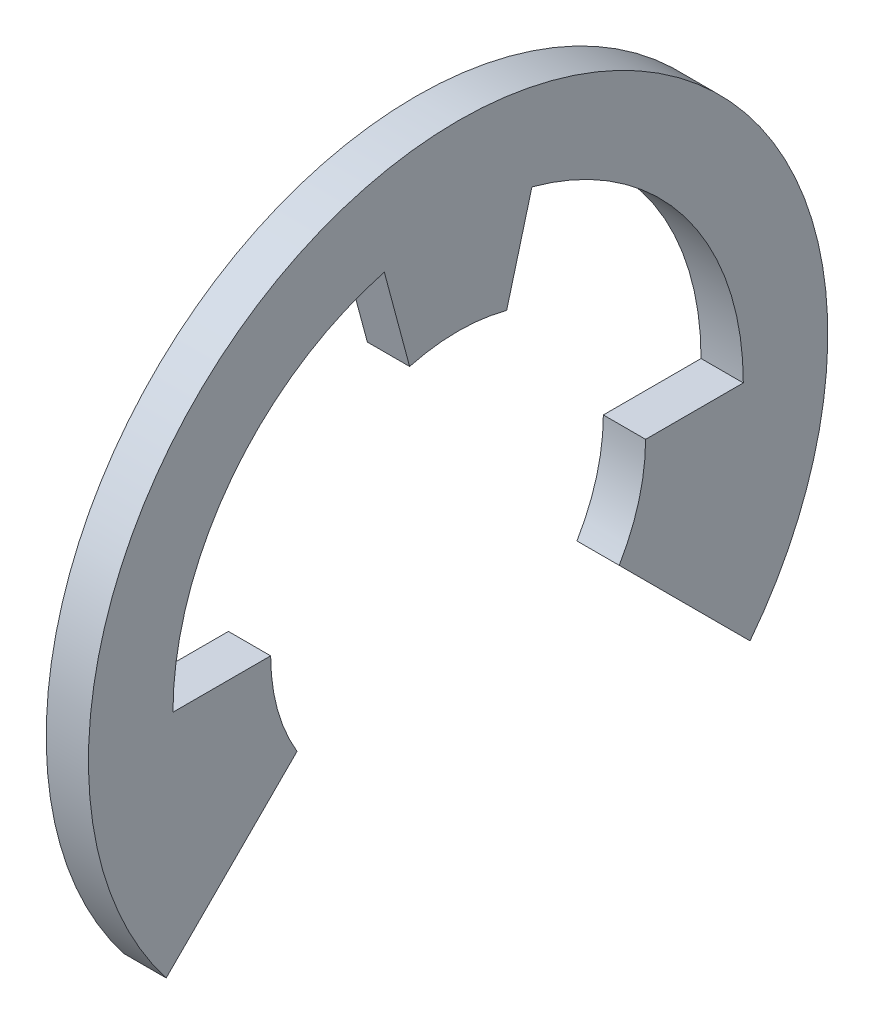
SolidWorks part; units mm, degrees
ref_plane "Front Plane" through (0, 0, 0) normal (0, 0, 1) x (1, 0, 0)
ref_plane "Top Plane" through (0, 0, 0) normal (0, 1, 0) x (1, 0, 0)
ref_plane "Right Plane" through (0, 0, 0) normal (1, 0, 0) x (0, 0, -1)
sketch "Sketch1" plane through (0, 0, 0) normal (1, 0, 0) x (0, 0, -1)
  line L0 (-3.55, 0) -> (-5.4, 0)
  line L1 (-0.9188, 3.429) -> (-1.3976, 5.216)
  line L2 (3.55, 0) -> (5.4, 0)
  line L3 (1.3976, 5.216) -> (0.9188, 3.429)
  line L4 (-3.05, -1.8166) -> (-5.5279, -4.2945)
  line L5 (3.05, -1.8166) -> (5.5279, -4.2945)
  line L9 (0, 0) -> (0, 7) construction
  arc A0 (-3.55, 0) -> (-3.05, -1.8166) centre (0, 0) ccw
  arc A1 (5.5279, -4.2945) -> (-5.5279, -4.2945) centre (0, 0) ccw
  arc A2 (5.4, 0) -> (1.3976, 5.216) centre (0, 0) ccw
  arc A3 (0.9188, 3.429) -> (-0.9188, 3.429) centre (0, 0) ccw
  arc A4 (-1.3976, 5.216) -> (-5.4, 0) centre (0, 0) ccw
  arc A5 (3.05, -1.8166) -> (3.55, 0) centre (0, 0) ccw
  circle A6 centre (0, 0) radius 3.55 construction
  dimension "D1" = 30
  dimension "D2" = 90
  dimension "REE_D" = 14
  dimension "REE_D_s" = 7.1
  dimension "REE_B_s" = 1.6
  dimension "REE_H" = 6.1
extrude "Boss-Extrude1" add sketch "Sketch1" along normal blind 0.8
